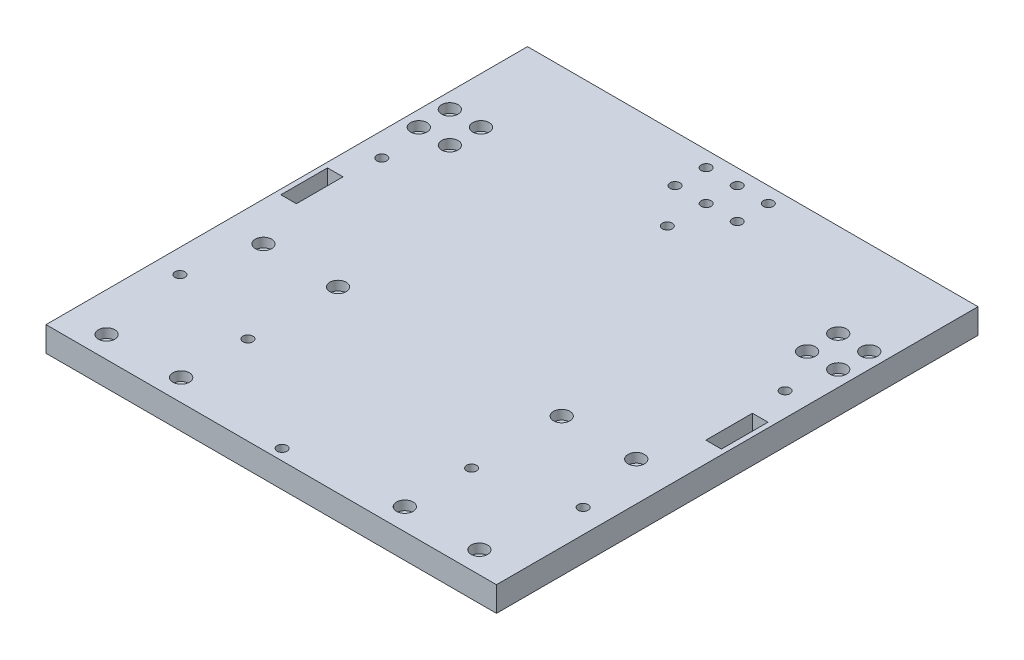
SolidWorks part; units mm, degrees
ref_plane "Front Plane" through (0, 0, 0) normal (0, 0, 1) x (1, 0, 0)
ref_plane "Top Plane" through (0, 0, 0) normal (0, 1, 0) x (1, 0, 0)
ref_plane "Right Plane" through (0, 0, 0) normal (1, 0, 0) x (0, 0, -1)
sketch "Sketch1" plane through (0, 0, 0) normal (0, 1, 0) x (1, 0, 0)
  line L0 (0, -77.5) -> (0, 77.5) construction
  line L5 (-72.5, -77.5) -> (72.5, -77.5)
  line L6 (-72.5, -77.5) -> (-72.5, 77.5)
  line L7 (-72.5, 77.5) -> (72.5, 77.5)
  line L8 (72.5, -77.5) -> (72.5, 77.5)
  line L9 (-72.5, -77.5) -> (72.5, 77.5) construction
  line L10 (-72.5, 77.5) -> (72.5, -77.5) construction
  line L11 (-72.5, 0) -> (72.5, 0) construction
  line L12 (-72.5, -70.5) -> (-60, -70.5) construction
  line L13 (-60, -77.5) -> (-60, -70.5) construction
  line L14 (-60, -70.5) -> (-60, -20) construction
  line L15 (-60, -70.5) -> (-36, -70.5) construction
  line L16 (-60, -20) -> (-36, -20) construction
  line L17 (-34.9494, 77.5) -> (-34.9494, 47.5) construction
  line L18 (-72.5, 47.5) -> (-67.5, 47.5) construction
  line L19 (-67.5, 47.5) -> (-67.5, 37.5) construction
  line L20 (-67.5, 37.5) -> (-57.5, 37.5) construction
  line L21 (-67.5, 47.5) -> (-57.5, 47.5) construction
  line L22 (-10, 77.5) -> (10, 77.5)
  line L23 (0, 27.9596) -> (-27.5, 27.9596) construction
  line L28 (2.5427, -77.5) -> (2.5427, -74) construction
  line L29 (36, -77.5) -> (36, -49) construction
  line L30 (-36, -49) -> (-36, -42) construction
  line L31 (-64.9, -42) -> (64.9, -42)
  line L32 (-64.9, -42) -> (-64.9, 23) construction
  line L33 (64.9, -42) -> (64.9, 50) construction
  line L34 (12.5059, -42) -> (12.5059, 4) construction
  line L35 (64.9, 4) -> (68.4, 4) construction
  line L36 (68.4, 4) -> (68.4, 11.5) construction
  line L37 (68.4, 11.5) -> (70.9, 11.5) construction
  line L38 (-65.9, 11.5) -> (-70.9, 11.5)
  line L39 (65.9, -3.5) -> (70.9, -3.5)
  line L40 (65.9, -3.5) -> (65.9, 11.5)
  line L41 (65.9, 11.5) -> (70.9, 11.5)
  line L42 (70.9, -3.5) -> (70.9, 11.5)
  line L43 (65.9, -3.5) -> (70.9, 11.5) construction
  line L44 (65.9, 11.5) -> (70.9, -3.5) construction
  line L45 (-70.9, -3.5) -> (-70.9, 11.5)
  line L46 (-65.9, -3.5) -> (-70.9, -3.5)
  line L47 (-65.9, -3.5) -> (-65.9, 11.5)
  line L48 (-10, 77.5) -> (-10, 72.5) construction
  line L49 (10, 77.5) -> (10, 62.5) construction
  circle A0 centre (-60, -70.5) radius 1.6
  circle A1 centre (-36, -70.5) radius 1.6
  circle A2 centre (-36, -20) radius 1.6
  circle A3 centre (-60, -20) radius 1.6
  circle A4 centre (60, -70.5) radius 1.6
  circle A5 centre (36, -70.5) radius 1.6
  circle A6 centre (36, -20) radius 1.6
  circle A7 centre (60, -20) radius 1.6
  circle A8 centre (-67.5, 47.5) radius 1.6
  circle A9 centre (-57.5, 47.5) radius 1.6
  circle A10 centre (-57.5, 37.5) radius 1.6
  circle A11 centre (-67.5, 37.5) radius 1.6
  circle A12 centre (67.5, 47.5) radius 1.6
  circle A13 centre (57.5, 47.5) radius 1.6
  circle A14 centre (57.5, 37.5) radius 1.6
  circle A15 centre (67.5, 37.5) radius 1.6
  circle A16 centre (0, -74) radius 1.6
  circle A17 centre (36, -49) radius 1.6
  circle A18 centre (-36, -49) radius 1.6
  circle A19 centre (-64.9, -42) radius 1.6
  circle A20 centre (-64.9, 23) radius 1.6
  circle A21 centre (0, 50) radius 1.6
  circle A22 centre (64.9, -42) radius 1.6
  circle A23 centre (64.9, 23) radius 1.6
  circle A24 centre (-10, 72.5) radius 1.6
  circle A25 centre (0, 72.5) radius 1.6
  circle A26 centre (10, 62.5) radius 1.6
  circle A27 centre (0, 62.5) radius 1.6
  circle A28 centre (-10, 62.5) radius 1.6
  circle A29 centre (10, 72.5) radius 1.6
  point P0 (0, 0)
  point P50 (0, 77.5)
  point P65 (0, -42)
extrude "Boss-Extrude1" add sketch "Sketch1" along normal blind 8
ref_plane "Plane1" through (0, 8, 0) normal (0, 1, 0) x (1, 0, 0)
sketch "Sketch2" plane through (0, 8, 0) normal (0, 1, 0) x (1, 0, 0)
  line L0 (0, -4.4) -> (0, 4.4) construction
  circle A0 centre (-57.5, 47.5) radius 2.65
  circle A1 centre (-67.5, 47.5) radius 2.65
  circle A2 centre (-57.5, 37.5) radius 2.65
  circle A3 centre (-67.5, 37.5) radius 2.65
  circle A4 centre (67.5, 47.5) radius 2.65
  circle A5 centre (57.5, 47.5) radius 2.65
  circle A6 centre (57.5, 37.5) radius 2.65
  circle A7 centre (67.5, 37.5) radius 2.65
  circle A8 centre (-36, -70.5) radius 2.65
  circle A9 centre (-60, -70.5) radius 2.65
  circle A10 centre (-36, -20) radius 2.65
  circle A11 centre (-60, -20) radius 2.65
  circle A12 centre (36, -70.5) radius 2.65
  circle A13 centre (60, -70.5) radius 2.65
  circle A14 centre (36, -20) radius 2.65
  circle A15 centre (60, -20) radius 2.65
extrude "Cut-Extrude1" cut sketch "Sketch2" against normal blind 3
sketch "Sketch3" plane through (0, 0, 0) normal (0, 1, 0) x (1, 0, 0)
  line L0 (0, -4.4) -> (0, 4.4) construction
  circle A0 centre (0, 50) radius 2.65
  circle A1 centre (-64.9, 23) radius 2.65
  circle A2 centre (-64.9, -42) radius 2.65
  circle A3 centre (-36, -49) radius 2.65
  circle A4 centre (0, -74) radius 2.65
  circle A5 centre (36, -49) radius 2.65
  circle A6 centre (64.9, -42) radius 2.65
  circle A7 centre (64.9, 23) radius 2.65
extrude "Cut-Extrude3" cut sketch "Sketch3" along normal blind 3
